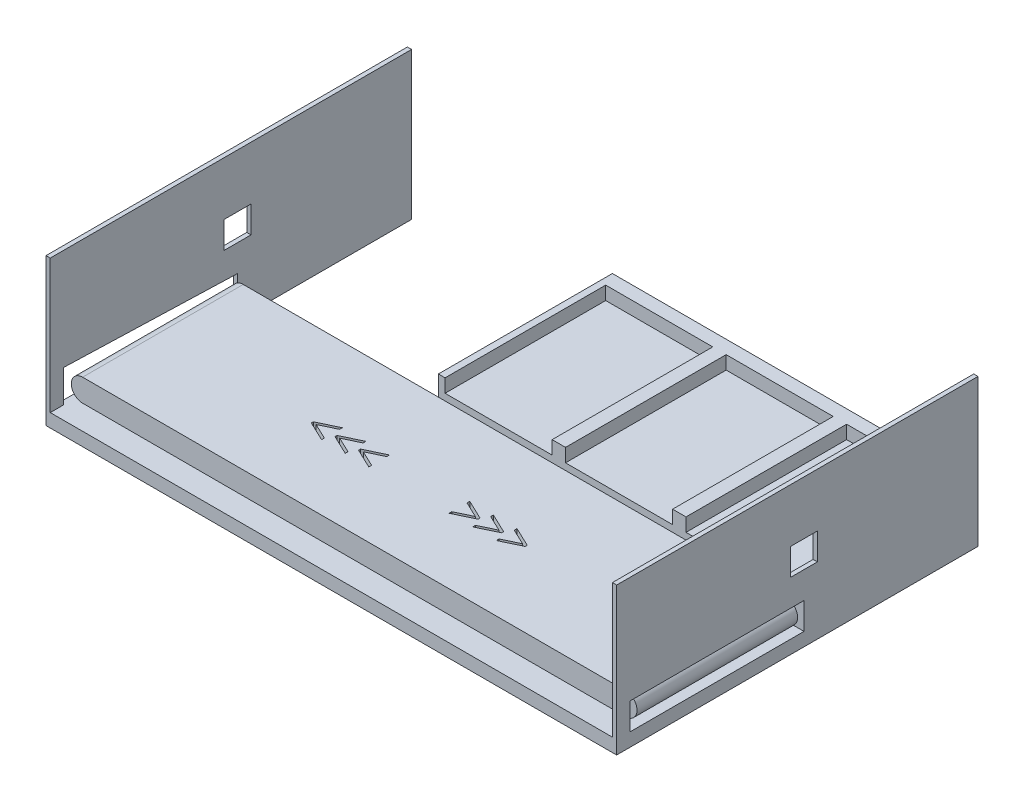
SolidWorks part; units mm, degrees
ref_plane "Front Plane" through (0, 0, 0) normal (0, 0, 1) x (1, 0, 0)
ref_plane "Top Plane" through (0, 0, 0) normal (0, 1, 0) x (1, 0, 0)
ref_plane "Right Plane" through (0, 0, 0) normal (1, 0, 0) x (0, 0, -1)
sketch "SingleLot" plane through (0, 0, 0) normal (0, 1, 0) x (1, 0, 0)
  line L0 (5, 70) -> (0, 70)
  line L1 (5, 70) -> (85, 70) construction
  line L2 (5, 70) -> (5, 190)
  line L3 (5, 190) -> (85, 190)
  line L4 (85, 70) -> (85, 190)
  line L5 (0, 70) -> (0, 200)
  line L6 (0, 200) -> (90, 200)
  line L7 (90, 200) -> (90, 70)
  line L8 (90, 70) -> (85, 70)
  dimension "D1" = 80
  dimension "D2" = 120
  dimension "D3" = 5
  dimension "D4" = 5
  dimension "D5" = 10
  dimension "D6" = 70
  dimension "D7" = 70
extrude "Parking" add sketch "SingleLot" along normal blind 10
pattern_linear "Parkings" count 3 spacing 90 along (1, 0, 0) of "Parking"
sketch "Wall" plane through (270, 0, 0) normal (1, 0, 0) x (0, 0, -1)
  line L3 (-70, 80) -> (200, 80)
  line L4 (200, 0) -> (200, 80)
  line L9 (70, 0) -> (70, -20)
  line L11 (200, 0) -> (200, -20)
  line L12 (200, -20) -> (70, -20)
  line L14 (70, 0) -> (-60, 0)
  line L18 (-70, -20) -> (-60, -20)
  line L19 (-60, 0) -> (-60, -20)
  line L20 (-70, 80) -> (-70, -20)
  dimension "D6" = 10
  dimension "D1" = 100
  dimension "D2" = 130
  dimension "D7" = 20
extrude "RightWall" add sketch "Wall" along normal blind 3.175
sketch "Sketch5" plane through (0, 0, 0) normal (0, -1, 0) x (1, 0, 0)
  line L1 (270, -70) -> (0, -70)
  line L2 (270, -70) -> (270, -200)
  line L3 (270, -200) -> (0, -200)
  line L5 (0, -200) -> (0, -70)
extrude "ParkingBottom" add sketch "Sketch5" along normal blind 20
ref_plane "BeltStartPlane" through (0, 0, -65) normal (0, 0, 1) x (1, 0, 0)
sketch "Sketch15" plane through (0, 0, -65) normal (0, 0, 1) x (1, 0, 0)
  line L0 (-140.825, 0) -> (265, 0)
  line L1 (-140.825, -16.825) -> (265, -16.825)
  line L2 (265, 10) -> (265, -16.825) construction
  line L3 (-140.825, 0) -> (-140.825, -20) construction
  line L4 (273.175, -20) -> (0, -20) construction
  line L6 (62.0875, 0) -> (62.0875, -16.825) construction
  line L8 (0, 10) -> (0, -20) construction
  arc A0 (-140.825, 0) -> (-140.825, -16.825) centre (-140.825, -8.4125) ccw
  arc A1 (265, 0) -> (265, -16.825) centre (265, -8.4125) cw
  dimension "D1" = 3.175
  dimension "D2" = 140.825
extrude "Belt" add sketch "Sketch15" along normal blind 120
sketch "Sketch16" plane through (0, 0, 0) normal (0, 1, 0) x (1, 0, 0)
  text T0 "<<<       >>>" font "Century Gothic" height in points 80
  point P1 (-27.3809, -8.8688)
  point P2 (0, 0)
extrude "<<>>Sign" cut sketch "Sketch16" against normal up to next (16.825 mm away)
sketch "Sketch17" plane through (0, -20, 0) normal (0, -1, 0) x (1, 0, 0)
  line L0 (0, -70) -> (0, -200) construction
  line L1 (0, -200) -> (273.175, -200)
  line L2 (-150, -70) -> (-150, 70)
  line L3 (-150, 70) -> (273.175, 70)
  line L4 (273.175, -200) -> (273.175, 70)
  line L5 (273.175, -70) -> (273.175, -200) construction
  line L6 (0, -70) -> (0, -200)
  line L7 (0, -70) -> (-150, -70)
  dimension "D1" = 150
extrude "FloorBase" add sketch "Sketch17" along normal blind 10
sketch "Sketch19" plane through (-150, 0, 0) normal (-1, 0, 0) x (0, 0, 1)
  line L0 (60, -20) -> (60, 4.203)
  line L1 (70, -30) -> (-200, -30)
  line L2 (70, -30) -> (70, 80)
  line L3 (70, 80) -> (-200, 80)
  line L4 (-200, -30) -> (-200, 80)
  line L5 (60, 4.203) -> (-70, 0)
  line L7 (-70, 0) -> (-70, -20)
  line L9 (70, -20) -> (-70, -20) construction
  line L10 (60, -20) -> (-70, -20)
  dimension "D1" = 10
  dimension "D2" = 20
extrude "LeftWall" add sketch "Sketch19" along normal blind 3.175
sketch "Sketch2" plane through (273.175, 0, 0) normal (1, 0, 0) x (0, 0, -1)
  line L1 (80, 40) -> (60, 40)
  line L2 (80, 40) -> (80, 20)
  line L3 (80, 20) -> (60, 20)
  line L4 (60, 40) -> (60, 20)
  line L7 (70, 10) -> (70, 0) construction
  line L8 (70, 10) -> (200, 10) construction
  dimension "D1" = 20
  dimension "D2" = 20
  dimension "D3" = 10
  dimension "D4" = 10
extrude "LaserHole" cut sketch "Sketch2" against normal up to vertex (426.35 mm away) up to point (-153.175, -30, -200)
